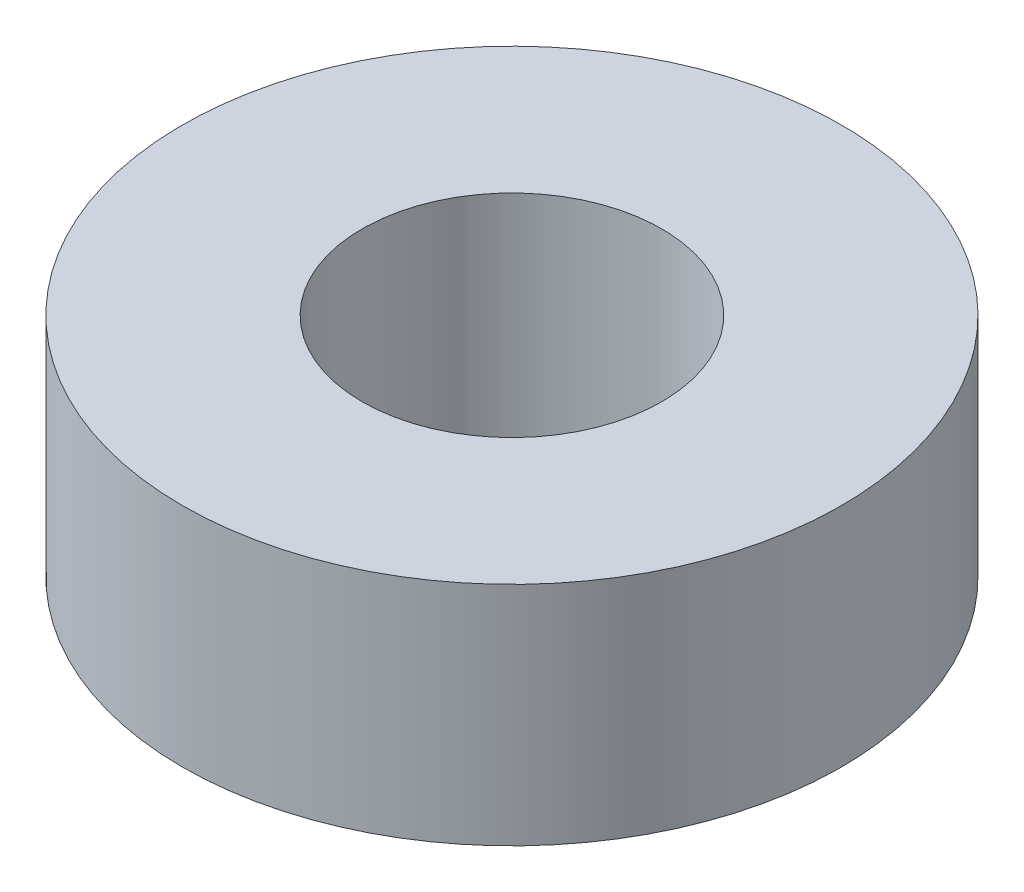
SolidWorks part; units mm, degrees
ref_plane "Front Plane" through (0, 0, 0) normal (0, 0, 1) x (1, 0, 0)
ref_plane "Top Plane" through (0, 0, 0) normal (0, 1, 0) x (1, 0, 0)
ref_plane "Right Plane" through (0, 0, 0) normal (1, 0, 0) x (0, 0, -1)
sketch "Sketch1" plane through (0, 0, 0) normal (0, 1, 0) x (1, 0, 0)
  circle A0 centre (0, 0) radius 7.9375
  circle A1 centre (0, 0) radius 17.4625
  dimension "D1" = 15.875
  dimension "D2" = 34.925
extrude "Boss-Extrude1" add sketch "Sketch1" along normal blind 12
